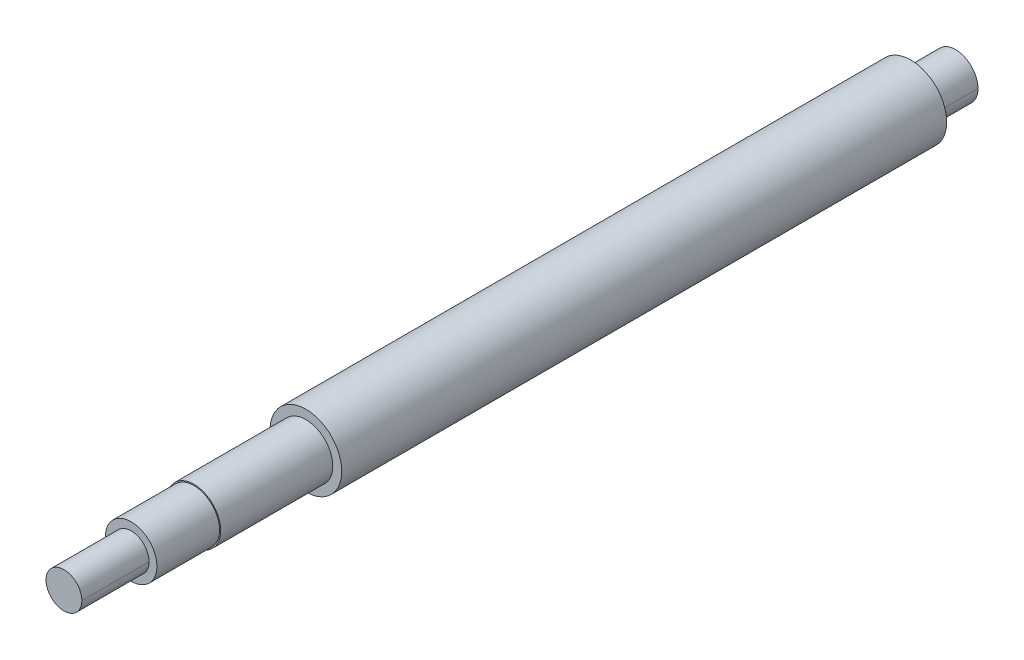
SolidWorks part; units mm, degrees
ref_plane "정면" through (0, 0, 0) normal (0, 0, 1) x (1, 0, 0)
ref_plane "윗면" through (0, 0, 0) normal (0, 1, 0) x (1, 0, 0)
ref_plane "우측면" through (0, 0, 0) normal (1, 0, 0) x (0, 0, -1)
sketch "스케치1" plane through (0, 0, 0) normal (0, 0, 1) x (1, 0, 0)
  circle A0 centre (0, 0) radius 5
  dimension "D1" = 10
extrude "보스-돌출1" add sketch "스케치1" along normal blind 10
sketch "스케치2" plane through (0, 0, 10) normal (0, 0, 1) x (1, 0, 0)
  circle A0 centre (0, 0) radius 8
  dimension "D1" = 16
extrude "보스-돌출2" add sketch "스케치2" along normal blind 135
sketch "스케치3" plane through (0, 0, 145) normal (0, 0, 1) x (1, 0, 0)
  circle A0 centre (0, 0) radius 6
  dimension "D1" = 12
extrude "보스-돌출3" add sketch "스케치3" along normal blind 25
sketch "스케치4" plane through (0, 0, 170) normal (0, 0, 1) x (1, 0, 0)
  circle A0 centre (0, 0) radius 5.75
  dimension "D1" = 11.5
extrude "보스-돌출4" add sketch "스케치4" along normal blind 14
sketch "스케치5" plane through (0, 0, 184) normal (0, 0, 1) x (1, 0, 0)
  circle A0 centre (0, 0) radius 4
  dimension "D1" = 8
extrude "보스-돌출5" add sketch "스케치5" along normal blind 15
split line "분할선1"
